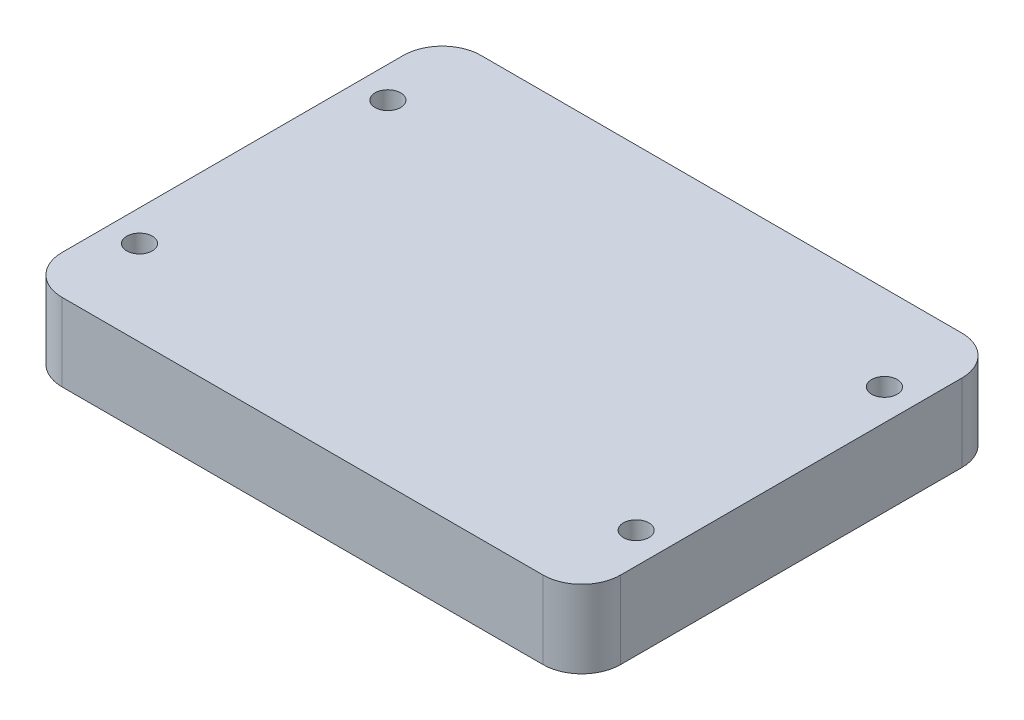
SolidWorks part; units mm, degrees
ref_plane "前视基准面" through (0, 0, 0) normal (0, 0, 1) x (1, 0, 0)
ref_plane "上视基准面" through (0, 0, 0) normal (0, 1, 0) x (1, 0, 0)
ref_plane "右视基准面" through (0, 0, 0) normal (1, 0, 0) x (0, 0, -1)
sketch "草图1" plane through (0, 0, 0) normal (0, 1, 0) x (1, 0, 0)
  line L1 (-36, 27) -> (36, 27)
  line L2 (-36, 27) -> (-36, -27)
  line L3 (-36, -27) -> (36, -27)
  line L4 (36, 27) -> (36, -27)
  line L5 (-36, 27) -> (36, -27) construction
  line L6 (-36, -27) -> (36, 27) construction
  point P0 (0, 0)
  dimension "D1" = 72
  dimension "D2" = 54
extrude "凸台-拉伸1" add sketch "草图1" along normal blind 10
sketch "草图2" plane through (0, 10, 0) normal (0, 1, 0) x (1, 0, 0)
  line L1 (-32, 16) -> (32, 16) construction
  line L2 (-32, 16) -> (-32, -16) construction
  line L3 (-32, -16) -> (32, -16) construction
  line L4 (32, 16) -> (32, -16) construction
  line L5 (-32, 16) -> (32, -16) construction
  line L6 (-32, -16) -> (32, 16) construction
  circle A0 centre (-32, 16) radius 1.65
  circle A1 centre (32, 16) radius 1.65
  circle A2 centre (32, -16) radius 1.65
  circle A3 centre (-32, -16) radius 1.65
  point P0 (0, 0)
  dimension "D3" = 3.3
  dimension "D4" = 3.3
  dimension "D5" = 3.3
  dimension "D6" = 3.3
  dimension "D1" = 32
  dimension "D2" = 64
extrude "切除-拉伸1" cut sketch "草图2" against normal through all both and the other way through all
fillet "圆角1" radius 5 4 edges at (36, 5, -27) (-36, 5, -27) (-36, 5, 27) (36, 5, 27)
